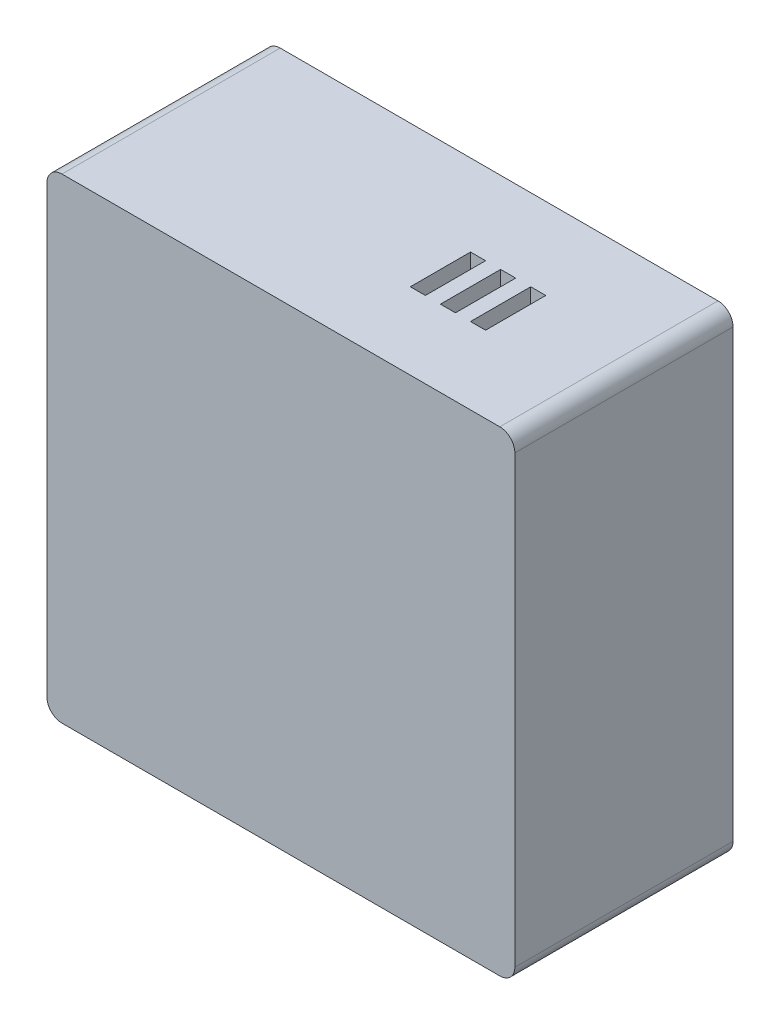
SolidWorks part; units mm, degrees
ref_plane "前视基准面" through (0, 0, 0) normal (0, 0, 1) x (1, 0, 0)
ref_plane "上视基准面" through (0, 0, 0) normal (0, 1, 0) x (1, 0, 0)
ref_plane "右视基准面" through (0, 0, 0) normal (1, 0, 0) x (0, 0, -1)
ref_plane "基准面1" through (0, 0, 0) normal (0, 0, 1) x (1, 0, 0)
sketch "草图2" plane through (0, 0, 0) normal (0, 0, 1) x (1, 0, 0)
  line L0 (-29.2051, -29.7131) -> (1.8873, -29.7131)
  line L1 (-27.3051, -27.8131) -> (-0.0127, -27.8131) construction
  line L2 (-27.3051, -27.8131) -> (-27.3051, -0.0127) construction
  line L3 (-27.3051, -0.0127) -> (-0.0127, -0.0127) construction
  line L4 (-0.0127, -27.8131) -> (-0.0127, -0.0127) construction
  line L5 (1.8873, -29.7131) -> (1.8873, 1.8873)
  line L6 (-29.2051, 1.8873) -> (1.8873, 1.8873)
  line L7 (-29.2051, -29.7131) -> (-29.2051, 1.8873)
  dimension "D1" = 1.9
extrude "凸台-拉伸1" add sketch "草图2" along normal blind 1.5
sketch "草图3" plane through (0, 0, 0) normal (0, 0, -1) x (-1, 0, 0)
  circle A4 centre (20.2, -2.16) radius 0.85
  circle A5 centre (7.24, -25.6501) radius 0.85
  circle A6 centre (20.2, -2.16) radius 1.9
  circle A7 centre (7.24, -25.6501) radius 1.9
  dimension "D1" = 1.7
  dimension "D2" = 1.7
  dimension "D3" = 3.8
  dimension "D4" = 3.8
extrude "凸台-拉伸2" add sketch "草图3" along normal up to surface (2 mm away)
sketch "草图4" plane through (0, 0, 0) normal (0, 0, -1) x (-1, 0, 0)
  line L4 (29.2051, -29.7131) -> (29.2051, 1.8873)
  line L5 (29.2051, 1.8873) -> (-1.8873, 1.8873)
  line L6 (-1.8873, 1.8873) -> (-1.8873, -29.7131)
  line L7 (-1.8873, -29.7131) -> (29.2051, -29.7131)
  line L8 (29.2051, -29.7131) -> (29.2051, 1.8873)
  line L9 (29.2051, 1.8873) -> (-1.8873, 1.8873)
  line L10 (-1.8873, 1.8873) -> (-1.8873, -29.7131)
  line L11 (-1.8873, -29.7131) -> (29.2051, -29.7131)
  line L12 (4.5964, -28.2004) -> (22.7086, -28.2004)
  line L13 (27.6924, -23.2166) -> (27.6924, -4.5964)
  line L14 (22.7086, 0.3873) -> (-0.3873, 0.3873)
  line L15 (-0.3873, 0.3873) -> (-0.3873, -23.2166)
  line L16 (27.7051, -28.2131) -> (27.7051, 0.3873)
  line L17 (27.7051, 0.3873) -> (-0.3873, 0.3873)
  line L18 (-0.3873, 0.3873) -> (-0.3873, -28.2131)
  line L19 (-0.3873, -28.2131) -> (27.7051, -28.2131)
  line L20 (27.7051, -28.2131) -> (27.7051, 0.3873)
  line L21 (27.7051, 0.3873) -> (-0.3873, 0.3873)
  line L22 (-0.3873, 0.3873) -> (-0.3873, -28.2131)
  line L23 (-0.3873, -28.2131) -> (27.7051, -28.2131)
  line L24 (5.0127, -27.8004) -> (22.2924, -27.8004)
  line L25 (27.2924, -22.8004) -> (27.2924, -5.0127)
  line L26 (22.2924, -0.0127) -> (0.0127, -0.0127)
  line L27 (0.0127, -0.0127) -> (0.0127, -22.8004)
  line L28 (5.0127, -27.8004) -> (22.2924, -27.8004) construction
  line L29 (27.2924, -22.8004) -> (27.2924, -5.0127) construction
  line L30 (22.2924, -0.0127) -> (0.0127, -0.0127) construction
  line L31 (0.0127, -0.0127) -> (0.0127, -22.8004) construction
  line L32 (43.6634, -13.9129) -> (34.2209, -13.9129) construction
  line L33 (25.3089, -2.0129) -> (2.0089, -2.0129) construction
  line L34 (25.3089, -2.0129) -> (25.3089, -25.8129) construction
  line L35 (25.3089, -25.8129) -> (2.0089, -25.8129) construction
  line L36 (2.0089, -2.0129) -> (2.0089, -25.8129) construction
  line L37 (13.6589, -36.3327) -> (13.6589, -48.6369) construction
  arc A0 (27.6924, -23.2166) -> (22.7086, -28.2004) centre (27.3051, -27.8131) ccw
  arc A1 (22.7086, 0.3873) -> (27.6924, -4.5964) centre (27.3051, 0) ccw
  arc A2 (4.5964, -28.2004) -> (-0.3873, -23.2166) centre (0, -27.8131) ccw
  arc A3 (27.2924, -22.8004) -> (22.2924, -27.8004) centre (27.3051, -27.8131) ccw
  arc A4 (22.2924, -0.0127) -> (27.2924, -5.0127) centre (27.3051, 0) ccw
  arc A5 (5.0127, -27.8004) -> (0.0127, -22.8004) centre (0, -27.8131) ccw
  arc A6 (27.2924, -22.8004) -> (22.2924, -27.8004) centre (27.3051, -27.8131) ccw construction
  arc A7 (22.2924, -0.0127) -> (27.2924, -5.0127) centre (27.3051, 0) ccw construction
  arc A8 (5.0127, -27.8004) -> (0.0127, -22.8004) centre (0, -27.8131) ccw construction
  circle A9 centre (25.3089, -2.0129) radius 0.95
  circle A13 centre (25.3089, -25.8129) radius 0.9
  circle A14 centre (2.0089, -25.8129) radius 0.9
  point P33 (13.6589, -13.9129)
  point P47 (13.6589, -13.9129)
  dimension "D7" = 1.9
  dimension "D8" = 1.8
  dimension "D9" = 1.8
  dimension "D5" = 23.8
  dimension "D6" = 23.3
  dimension "D1" = 0
  dimension "D2" = 1.5
  dimension "D3" = 0
  dimension "D4" = 0.4
extrude "凸台-拉伸3" add sketch "草图4" along normal blind 13
sketch "草图5" plane through (-29.2051, 0, 0) normal (-1, 0, 0) x (0, 0, 1)
  line L0 (-14.5712, -13.9612) -> (-22.5695, -13.9612) construction
  line L1 (-5.2062, -9.7912) -> (-5.2062, -8.4752) construction
  line L3 (-4.6262, -9.7912) -> (-5.7862, -9.7912) construction
  line L6 (-3.4358, -18.5503) -> (-6.9766, -18.5503)
  line L7 (-3.4358, -18.5503) -> (-3.4358, -9.372)
  line L8 (-3.4358, -9.372) -> (-6.9766, -9.372)
  line L9 (-6.9766, -18.5503) -> (-6.9766, -9.372)
  line L10 (-3.4358, -18.5503) -> (-6.9766, -9.372) construction
  line L11 (-3.4358, -9.372) -> (-6.9766, -18.5503) construction
  circle A0 centre (-5.2062, -6.4093) radius 0.5
  point P5 (-5.2062, -9.7912)
  point P6 (-5.2062, -13.9612)
  point P11 (-6.4762, -18.4112)
  point P12 (-6.4762, -9.5112)
  point P14 (-5.2062, -13.9612)
  dimension "D1" = 1
extrude "切除-拉伸1" cut sketch "草图5" against normal up to next contours L7 L6 L9 L8 | A0
sketch "草图6" plane through (0, -29.7131, 0) normal (0, -1, 0) x (1, 0, 0)
  line L0 (-14.717, -6.8862) -> (-14.717, -15.5678) construction
  line L1 (-11.2014, -8.0862) -> (-18.2326, -8.0862) construction
  line L2 (1.8873, -13) -> (-29.2051, -13) construction
  line L3 (-16.9238, -13) -> (-12.5103, -13)
  line L4 (-16.9238, -13) -> (-16.9238, -4.7905)
  line L5 (-16.9238, -4.7905) -> (-12.5103, -4.7905)
  line L6 (-12.5103, -13) -> (-12.5103, -4.7905)
  point P6 (-14.717, -8.0862)
extrude "切除-拉伸2" cut sketch "草图6" against normal up to next
sketch "草图8" plane through (0, 1.8873, 0) normal (0, 1, 0) x (1, 0, 0)
  line L0 (-8.144, 7.5862) -> (-8.144, 3.5862)
  line L1 (-10.144, 7.5862) -> (-9.144, 7.5862)
  line L2 (-10.144, 7.5862) -> (-10.144, 3.5862)
  line L3 (-10.144, 3.5862) -> (-9.144, 3.5862)
  line L4 (-9.144, 7.5862) -> (-9.144, 3.5862)
  line L5 (-8.144, 7.5862) -> (-7.144, 7.5862)
  line L6 (-7.144, 7.5862) -> (-7.144, 3.5862)
  line L7 (-8.144, 3.5862) -> (-7.144, 3.5862)
  line L8 (-6.144, 7.5862) -> (-6.144, 3.5862)
  line L9 (-6.144, 7.5862) -> (-5.144, 7.5862)
  line L10 (-5.144, 7.5862) -> (-5.144, 3.5862)
  line L11 (-6.144, 3.5862) -> (-5.144, 3.5862)
  dimension "D1" = 1
  dimension "D2" = 4
  dimension "D3" = 3
extrude "切除-拉伸3" cut sketch "草图8" against normal up to next
fillet "圆角1" radius 1 4 edges at (-29.2051, 1.8873, -5.75) (1.8873, 1.8873, -5.75) (-29.2051, -29.7131, -5.75) (1.8873, -29.7131, -5.75)
fillet "圆角2" radius 0.8 4 edges at (-28.4487, -18.5503, -3.4358) (-28.4487, -9.372, -3.4358) (-28.4487, -9.372, -6.9766) (-28.4487, -18.5503, -6.9766)
